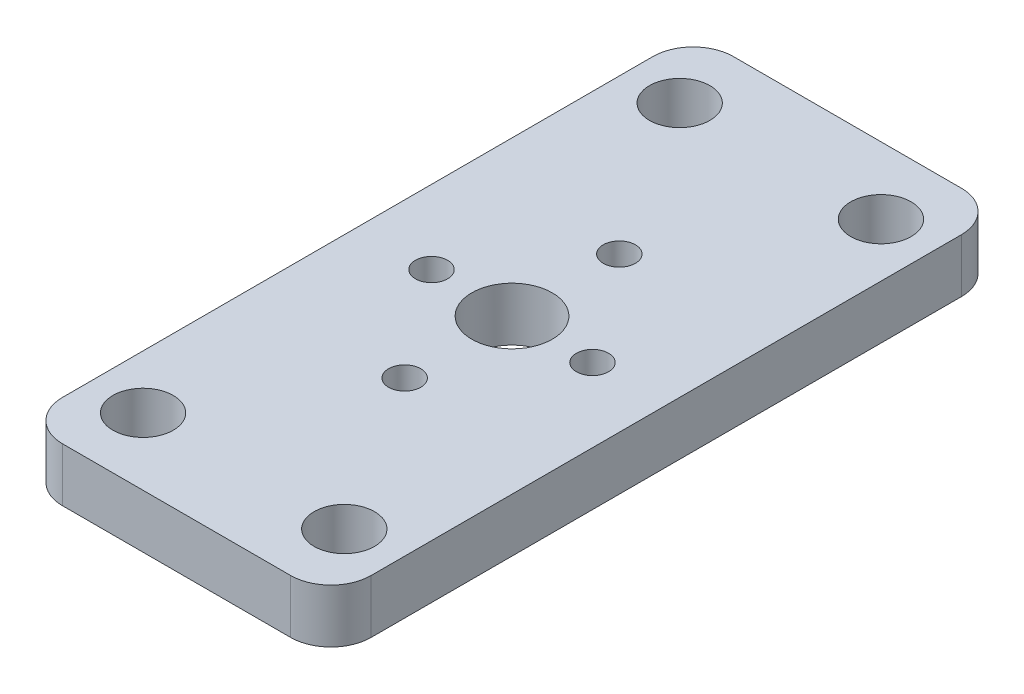
SolidWorks part; units mm, degrees
ref_plane "Front Plane" through (0, 0, 0) normal (0, 0, 1) x (1, 0, 0)
ref_plane "Top Plane" through (0, 0, 0) normal (0, 1, 0) x (1, 0, 0)
ref_plane "Right Plane" through (0, 0, 0) normal (1, 0, 0) x (0, 0, -1)
sketch "Sketch1" plane through (0, 0, 0) normal (0, 1, 0) x (1, 0, 0)
  line L1 (-11.5, -25) -> (11.5, -25)
  line L2 (-11.5, -25) -> (-11.5, 25)
  line L3 (-11.5, 25) -> (11.5, 25)
  line L4 (11.5, -25) -> (11.5, 25)
  line L5 (-11.5, -25) -> (11.5, 25) construction
  line L6 (-11.5, 25) -> (11.5, -25) construction
  point P0 (0, 0)
  dimension "D1" = 23
  dimension "D2" = 50
extrude "Boss-Extrude1" add sketch "Sketch1" along normal blind 4
hole_wizard "M4 Clearance Hole1" positions "Sketch2" profile "Sketch3" hole size "M4" standard "ANSI Metric" end condition through all
sketch "Sketch2" plane through (0, 4, 0) normal (0, 1, 0) x (1, 0, 0)
  line L0 (-11.5, 25) -> (-11.5, -25) construction
  line L1 (11.5, -25) -> (11.5, 25) construction
  line L2 (-7.5, 20) -> (-7.5, -20) construction
  point P0 (-7.5, 20)
  point P2 (7.5, 20)
  point P4 (-7.5, -20)
  point P6 (7.5, -20)
  point P19 (-7.5, 0)
  point P20 (-11.5, 0)
  dimension "D1" = 40
  dimension "D2" = 4
  dimension "D3" = 4
  dimension "D4" = 4
  dimension "D5" = 4
sketch "Sketch3" plane through (-7.5, 4, -20) normal (1, 0, 0) x (0, 0, 1)
  line L0 (0, 0) -> (0, 4)
  line L1 (0, 4) -> (2.25, 4)
  line L2 (2.25, 4) -> (2.25, 0)
  line L5 (2.25, 0) -> (0, 0)
  line L11 (0, -6.35) -> (0, 107.95) construction
  dimension "Thru Hole Dia." = 4.5
  dimension "Thru Hole Depth" = 4
fillet "Fillet1" radius 3 4 edges at (-11.5, 2, 25) (11.5, 2, 25) (11.5, 2, -25) (-11.5, 2, -25)
sketch "Sketch4" plane through (0, 0, 0) normal (0, 1, 0) x (1, 0, 0)
  line L0 (-6, 0) -> (6, 0) construction
  line L1 (0, 8) -> (0, -8) construction
  circle A0 centre (0, 0) radius 3
  point P7 (0, 0)
  point P9 (0, 0)
  dimension "D1" = 6
  dimension "D2" = 12
  dimension "D3" = 16
extrude "Cut-Extrude1" cut sketch "Sketch4" along normal blind 10
hole_wizard "CBORE for M2 Pan Head Machine Screw1" positions "Sketch7" profile "Sketch9" counterbore size "M2" standard "ANSI Metric" end condition through all
sketch "Sketch7" plane through (0, 0, 0) normal (0, -1, 0) x (-1, 0, 0)
  point P0 (0, -8)
  point P3 (-6, 0)
  point P6 (0, 8)
  point P9 (6, 0)
sketch "Sketch9" plane through (0, 0, 8) normal (1, 0, 0) x (0, 0, -1)
  line L0 (0, 0) -> (0, 4)
  line L1 (0, 4) -> (1.2, 4)
  line L3 (1.2, 4) -> (1.2, 1.6)
  line L4 (1.2, 1.6) -> (2.5, 1.6)
  line L5 (2.5, 1.6) -> (2.5, 0)
  line L7 (2.5, 0) -> (0, 0)
  line L11 (0, -6.35) -> (0, 107.95) construction
  dimension "Thru Hole Dia." = 2.4
  dimension "Thru Hole Depth" = 4
  dimension "C'Bore Dia." = 5
  dimension "C'Bore Depth" = 1.6
